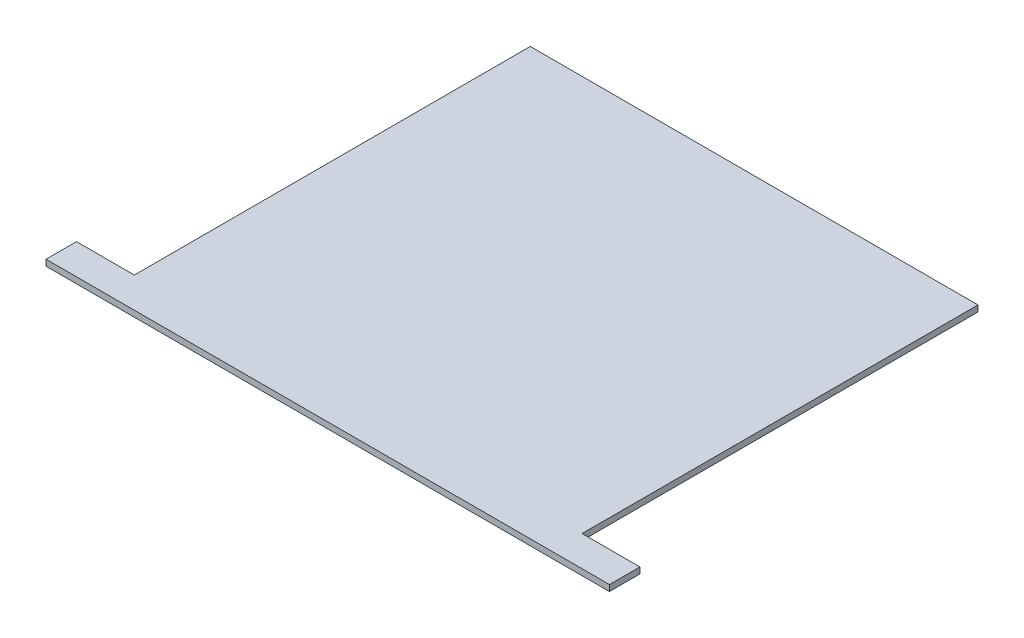
SolidWorks part; units mm, degrees
ref_plane "前视基准面" through (0, 0, 0) normal (0, 0, 1) x (1, 0, 0)
ref_plane "上视基准面" through (0, 0, 0) normal (0, 1, 0) x (1, 0, 0)
ref_plane "右视基准面" through (0, 0, 0) normal (1, 0, 0) x (0, 0, -1)
sketch "草图1" plane through (0, 0, 0) normal (0, 1, 0) x (1, 0, 0)
  line L1 (-53.9678, 27.3071) -> (131.0322, 27.3071)
  line L2 (-53.9678, 27.3071) -> (-53.9678, -112.6929)
  line L3 (-53.9678, -112.6929) -> (131.0322, -112.6929)
  line L4 (131.0322, 27.3071) -> (131.0322, -112.6929)
  dimension "D1" = 185
  dimension "D2" = 140
extrude "凸台-拉伸1" add sketch "草图1" along normal blind 2
sketch "草图3" plane through (0, 0, 0) normal (0, 1, 0) x (1, 0, 0)
  line L0 (131.0322, 27.3071) -> (-53.9678, 27.3071) construction
  line L1 (-53.9678, 27.3071) -> (-34.9678, 27.3071)
  line L2 (-53.9678, 27.3071) -> (-53.9678, -102.6929)
  line L3 (-53.9678, -102.6929) -> (-34.9678, -102.6929)
  line L4 (-34.9678, 27.3071) -> (-34.9678, -102.6929)
  line L5 (-53.9678, 27.3071) -> (-53.9678, -112.6929) construction
  line L6 (-53.9678, -112.6929) -> (131.0322, -112.6929) construction
  dimension "D1" = 19
  dimension "D2" = 10
extrude "切除-拉伸3" cut sketch "草图3" along normal through all
sketch "草图4" plane through (0, 0, 0) normal (0, 1, 0) x (1, 0, 0)
  line L0 (-53.9678, -112.6929) -> (131.0322, -112.6929) construction
  line L1 (131.0322, 27.3071) -> (112.0322, 27.3071)
  line L2 (131.0322, 27.3071) -> (131.0322, -102.6929)
  line L3 (131.0322, -102.6929) -> (112.0322, -102.6929)
  line L4 (112.0322, 27.3071) -> (112.0322, -102.6929)
  dimension "D1" = 10
  dimension "D2" = 19
extrude "切除-拉伸4" cut sketch "草图4" along normal through all
